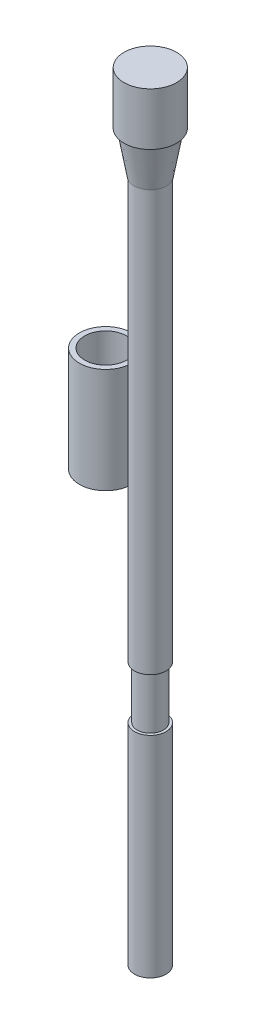
SolidWorks part; units mm, degrees
ref_plane "Front Plane" through (0, 0, 0) normal (0, 0, 1) x (1, 0, 0)
ref_plane "Top Plane" through (0, 0, 0) normal (0, 1, 0) x (1, 0, 0)
ref_plane "Right Plane" through (0, 0, 0) normal (1, 0, 0) x (0, 0, -1)
sketch "Sketch1" plane through (0, 0, 0) normal (0, 1, 0) x (1, 0, 0)
  circle A0 centre (0, 0) radius 25
  dimension "D1" = 50
extrude "Boss-Extrude2" add sketch "Sketch1" along normal blind 50
sketch "Sketch3" plane through (0, 0, 0) normal (0, -1, 0) x (1, 0, 0)
  circle A0 centre (0, 0) radius 22.5
  dimension "D1" = 45
extrude "Boss-Extrude4" add sketch "Sketch3" along normal blind 40 draft 10
sketch "Sketch5" plane through (0, -40, 0) normal (0, -1, 0) x (1, 0, 0)
  circle A0 centre (0, 0) radius 15
  dimension "D1" = 30
extrude "Boss-Extrude5" add sketch "Sketch5" along normal blind 400
ref_plane "Plane1" through (0, -300, 0) normal (0, 1, 0) x (1, 0, 0)
sketch "Sketch7" plane through (0, -300, 0) normal (0, 1, 0) x (1, 0, 0)
  circle A0 centre (-39.9636, -2.5231) radius 25
  dimension "D1" = 50
extrude "Boss-Extrude6" add sketch "Sketch7" along normal blind 100
sketch "Sketch8" plane through (0, -200, 0) normal (0, 1, 0) x (1, 0, 0)
  circle A0 centre (-39.9636, -2.5231) radius 20
  dimension "D1" = 40
extrude "Cut-Extrude1" cut sketch "Sketch8" against normal blind 100
sketch "Sketch10" plane through (0, -440, 0) normal (0, -1, 0) x (1, 0, 0)
  circle A0 centre (0, 0) radius 12.5
  dimension "D1" = 25
extrude "Boss-Extrude7" add sketch "Sketch10" along normal blind 50
sketch "Sketch11" plane through (0, -490, 0) normal (0, -1, 0) x (1, 0, 0)
  circle A0 centre (0, 0) radius 15
  dimension "D1" = 30
extrude "Boss-Extrude8" add sketch "Sketch11" along normal blind 200
